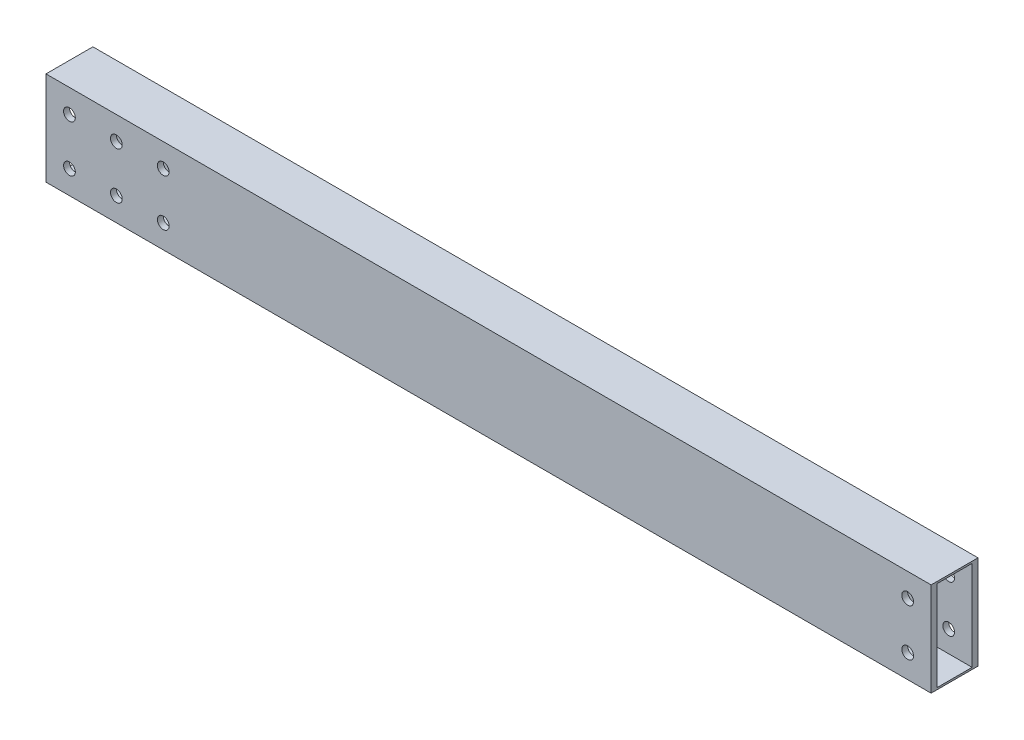
SolidWorks part; units mm, degrees
other "Markup1"
sketch "Sketch6" plane through (0, 0, 0) normal (0, 0, 1) x (1, 0, 0)
ref_plane "Front Plane" through (0, 0, 0) normal (0, 0, 1) x (1, 0, 0)
ref_plane "Top Plane" through (0, 0, 0) normal (0, 1, 0) x (1, 0, 0)
ref_plane "Right Plane" through (0, 0, 0) normal (1, 0, 0) x (0, 0, -1)
sketch "Sketch1" plane through (0, 0, 0) normal (1, 0, 0) x (0, 0, -1)
  line L1 (0, 0) -> (25.4, 0)
  line L2 (0, 0) -> (0, 50.8)
  line L3 (0, 50.8) -> (25.4, 50.8)
  line L4 (25.4, 0) -> (25.4, 50.8)
  dimension "D1" = 50.8
  dimension "D2" = 25.4
extrude "Boss-Extrude1" add sketch "Sketch1" along normal blind 479.3369
sketch "Sketch2" plane through (479.3369, 0, 0) normal (1, 0, 0) x (0, 0, -1)
  line L0 (25.4, 0) -> (25.4, 50.8) construction
  line L1 (3.175, 49.784) -> (22.225, 49.784)
  line L2 (3.175, 49.784) -> (3.175, 1.016)
  line L3 (3.175, 1.016) -> (22.225, 1.016)
  line L4 (22.225, 49.784) -> (22.225, 1.016)
  line L5 (0, 50.8) -> (0, 0) construction
  line L6 (25.4, 50.8) -> (0, 50.8) construction
  line L7 (0, 0) -> (25.4, 0) construction
  dimension "D1" = 3.175
  dimension "D2" = 3.175
  dimension "D3" = 1.016
  dimension "D4" = 1.016
extrude "Cut-Extrude1" cut sketch "Sketch2" against normal through all
sketch "Sketch5" plane through (0, 0, 0) normal (0, 0, 1) x (1, 0, 0)
  line L0 (0, 50.8) -> (0, 0) construction
  line L1 (479.3369, 50.8) -> (0, 50.8) construction
  line L3 (479.3369, 50.8) -> (479.3369, 0) construction
  circle A0 centre (12.7, 38.1) radius 3.175
  circle A1 centre (38.1, 38.1) radius 3.175
  circle A2 centre (12.7, 12.7) radius 3.175
  circle A3 centre (38.1, 12.7) radius 3.175
  circle A4 centre (63.5, 38.1) radius 3.175
  circle A5 centre (63.5, 12.7) radius 3.175
  circle A6 centre (466.6369, 38.1) radius 3.175
  circle A7 centre (466.6369, 12.7) radius 3.175
  dimension "D1" = 6.35
  dimension "D2" = 12.7
  dimension "D3" = 12.7
  dimension "D4" = 12.7
  dimension "D5" = 38.1
  dimension "D6" = 25.4
  dimension "D7" = 25.4
  dimension "D8" = 12.7
  dimension "D9" = 25.4
  dimension "D10" = 12.7
  dimension "D11" = 25.4
  dimension "D12" = 25.4
  dimension "D13" = 6.35
  dimension "D14" = 6.35
  dimension "D15" = 25.4
  dimension "D16" = 12.7
  dimension "D18" = 25.4
  dimension "D19" = 12.7
  dimension "D20" = 6.35
  dimension "D17" = 12.7
extrude "Cut-Extrude4" cut sketch "Sketch5" against normal through all both and the other way through all
